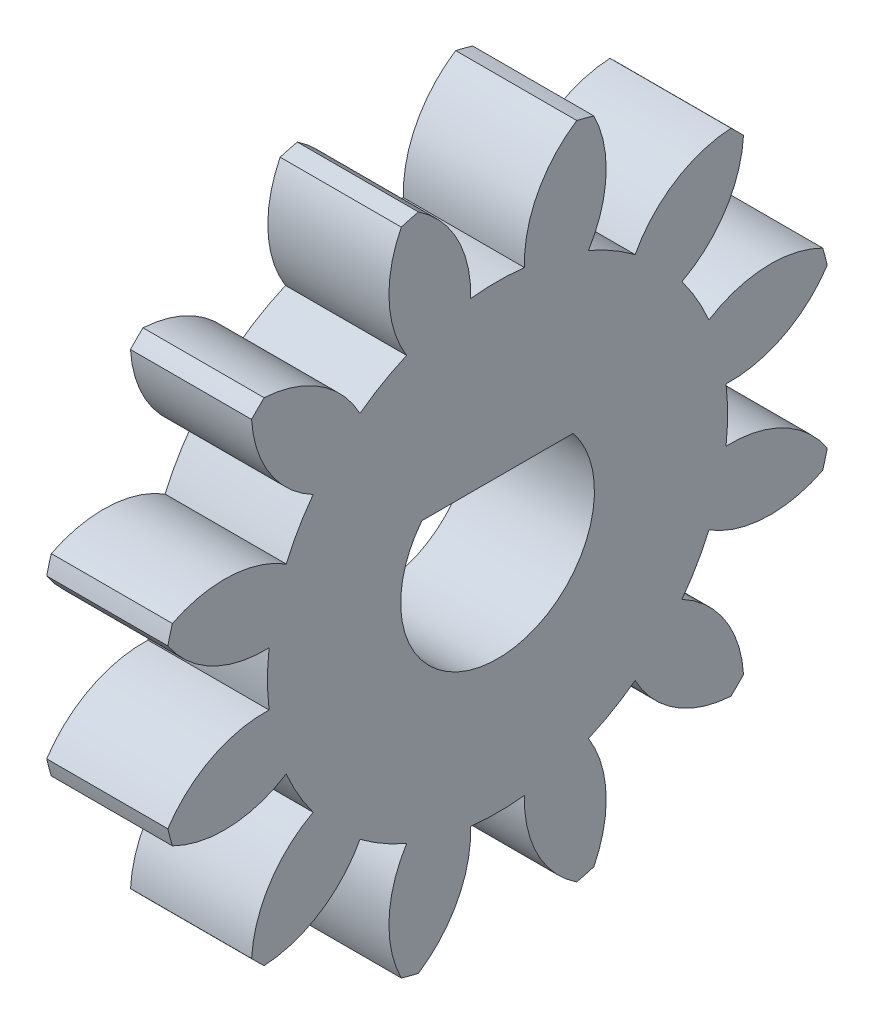
SolidWorks part; units mm, degrees
ref_plane "Plane1" through (0, 0, 0) normal (0, 0, 1) x (1, 0, 0)
ref_plane "Plane2" through (0, 0, 0) normal (0, 1, 0) x (1, 0, 0)
ref_plane "Plane3" through (0, 0, 0) normal (1, 0, 0) x (0, 0, -1)
sketch "HoldingSke" plane through (0, 0, 0) normal (0, 1, 0) x (1, 0, 0)
  line L0 (0, 0) -> (0.4891, -0.104)
  line L1 (-15, 0) -> (100, 0) construction
  line L2 (0, 0) -> (-2.1039, 2.3779)
  line L3 (0, 0) -> (-11.863, 4.5341)
  line L4 (0, 0) -> (8.4473, 1.7955)
  line L5 (0, 0) -> (-46.8476, -17.4728)
  line L6 (0, 0) -> (-4.1448, -2.7965)
  line L7 (-2.1039, 2.3779) -> (8.6586, 51.2059)
  line L8 (-76.2, 54.61) -> (-74.8, 54.61)
  line L9 (-71.009, 38.7566) -> (-53.1078, 45.2721)
  line L10 (-76.2, 71.12) -> (104.1128, 71.12)
  line L11 (0, 0) -> (-5, 0)
  line L12 (-76.2, 101.6) -> (-76.133, 101.6)
  line L13 (24.9733, 27.94) -> (52.9518, 28.4284)
  line L14 (24.9733, 27.94) -> (24.9743, 27.94)
  line L15 (24.9733, 27.94) -> (100.4006, 29.5858)
  line L16 (-63.627, -2) -> (-12.827, -2)
  circle A0 centre (0, 0) radius 4
  circle A1 centre (0, 0) radius 9.499
  circle A2 centre (0, 0) radius 37.5
  circle A3 centre (0, 0) radius 4
  dimension "MHD" = 18.998
  dimension "Hub_dia" = 75
  dimension "Bore" = 8
  dimension "MBD" = 8
  dimension "Num_teeth" = 12
  dimension "Pitch" = 0.5
  dimension "Overall_len" = 50
  dimension "Show_teeth" = 12
  dimension "Thickness" = 5
  dimension "OAL" = 50.0001
  dimension "T_dim" = 1.4
  dimension "Ap" = 20
  dimension "H" = 19.05
  dimension "Pitch_radius" = 180.3128
  dimension "Width" = 5
  dimension "Backlash" = 0.067
  dimension "Addendum_fac" = 1
  dimension "Dedendum_fac" = 1.25
  dimension "Clearance_fac" = 0.25
  dimension "Dedendum_add" = 0.001
  dimension "Module" = 2
sketch "BasProSke" plane through (0, 0, 0) normal (0, 1, 0) x (1, 0, 0)
  line L0 (-10, 0) -> (60, 0) construction
  line L1 (0, 0) -> (0, 14)
  line L2 (0, 0) -> (5, 0)
  line L3 (5, 0) -> (5, 14)
  line L4 (5, 14) -> (0, 14)
  dimension "Thickness" = 5
  dimension "Diameter" = 28
revolve "Base-Revolve" add sketch "BasProSke" angle 360 about L0
sketch "TooCutSke" plane through (0, 0, 0) normal (1, 0, 0) x (0, 0, -1)
  line L1 (0, 0) -> (0, 107) construction
  line L2 (0, 0) -> (-1.6834, 11.8813) construction
  line L3 (0, 0) -> (-6.1662, 23.0126) construction
  line L4 (-1.6834, 11.8813) -> (-3.0831, 11.5063) construction
  arc A0 (1.1119, 9.4337) -> (-1.1119, 9.4337) centre (0, 0) ccw
  arc A1 (3.2981, 13.6321) -> (-3.2981, 13.6321) centre (0, 0) ccw
  circle A2 centre (0, 0) radius 12 construction
  circle A3 centre (0, 0) radius 11.2763 construction
  arc A4 (-1.1119, 9.4337) -> (-3.2981, 13.6321) centre (-5.9089, 9.6042) ccw
  arc A5 (3.2981, 13.6321) -> (1.1119, 9.4337) centre (5.9089, 9.6042) ccw
  dimension "Root_dia" = 18.998
  dimension "Overcut_dia" = 28.0508
  dimension "Pitch_dia" = 24
  dimension "Base_dia" = 22.5526
  dimension "Flank_rad" = 4.8
  dimension "Half_ang" = 15
  dimension "Half_CT" = 1.4491
extrude "ToothCut" cut sketch "TooCutSke" along normal through all
fillet "Breaks" [suppressed] radius 0.04
fillet "RootFillets" [suppressed] radius 0.501
pattern_circular "TeethCuts" count 12 every 30 about axis through (-10, 0, 0) along (1, 0, 0) of "ToothCut", "RootFillets", "Breaks"
sketch "HubNeaOneSke" plane through (0, 0, 0) normal (-1, 0, 0) x (0, 0, 1)
  circle A0 centre (0, 0) radius 9.499
  dimension "Diameter" = 18.998
extrude "HubNearOne" [suppressed] add sketch "HubNeaOneSke" along normal blind 45.0001
sketch "HubNeaBotSke" plane through (0, 0, 0) normal (-1, 0, 0) x (0, 0, 1)
  circle A0 centre (0, 0) radius 9.499
  dimension "Diameter" = 18.998
extrude "HubNearBoth" [suppressed] add sketch "HubNeaBotSke" along normal blind 22.5
ref_plane "FarPln" through (5, 0, 0) normal (1, 0, 0) x (0, 0, -1)
sketch "HubFarSke" plane through (5, 0, 0) normal (1, 0, 0) x (0, 0, -1)
  circle A0 centre (0, 0) radius 9.499
  dimension "Diameter" = 18.998
extrude "HubFar" [suppressed] add sketch "HubFarSke" along normal blind 22.5
sketch "BorSke" plane through (0, 0, 0) normal (1, 0, 0) x (0, 0, -1)
  circle A0 centre (0, 0) radius 4
  dimension "Diameter" = 8
extrude "Bore" cut sketch "BorSke" along normal mid plane 100.0001
sketch "KeySke" plane through (0, 0, 0) normal (1, 0, 0) x (0, 0, -1)
  line L0 (-1.5, 0) -> (-1.5, 5.4)
  line L1 (-1.5, 5.4) -> (1.5, 5.4)
  line L2 (1.5, 5.4) -> (1.5, 0)
  line L3 (0, 0) -> (0, 34) construction
  line L4 (-1.5, 0) -> (1.5, 0)
  dimension "Offset" = 5.4
  dimension "Width" = 3
extrude "Keyway" [suppressed] cut sketch "KeySke" along normal mid plane 100.0001
pattern_circular "Keyway2" [suppressed] count 2 every 90 about axis through (-10, 0, 0) along (1, 0, 0)
sketch "Sketch1" plane through (5, 0, 0) normal (1, 0, 0) x (0, 0, -1)
  line L0 (-3.1225, 2.5) -> (3.1225, 2.5)
  circle A0 centre (0, 0) radius 4 construction
  arc A1 (3.1225, 2.5) -> (-3.1225, 2.5) centre (0, 0) ccw
  dimension "D1" = 2.5
extrude "Boss-Extrude1" add sketch "Sketch1" against normal blind 5
equation "' \"Module@HoldingSke\" = 6.35"
equation "' \"Num_teeth@HoldingSke\" = 12"
equation "' \"Ap@HoldingSke\" =  20"
equation "' \"Ap@HoldingSke\" = 20"
equation "' \"Width@HoldingSke\" = 0.5 * 25.4"
equation "' \"Hub_dia@HoldingSke\"= 1 * 25.4"
equation "' \"Hub_dia@HoldingSke\" = 1 * 25.4"
equation "' \"Overall_len@HoldingSke\" = 1.0 * 25.4"
equation "' \"Bore@HoldingSke\" = 0.75 * 25.4"
equation "' \"T_dim@HoldingSke\" = 0.1 * 25.4"
equation "' \"Width@KeySke\" = 0.25 * 25.4"
equation "' \"Show_teeth@HoldingSke\" = 13"
equation "' \"Backlash@HoldingSke\" = 0.009 * 25.4"
equation "' \"Addendum_fac@HoldingSke\" = 1.0"
equation "' \"Dedendum_fac@HoldingSke\" = 1.25"
equation "' \"Dedendum_add@HoldingSke\" = 0.00005 * 25.4"
equation "' \"Clearance_fac@HoldingSke\" = 0.25"
equation "\"Pitch@HoldingSke\" = 1 / \"Module@HoldingSke\""
equation "\"Overcut_dia@TooCutSke\" = (\"Num_teeth@HoldingSke\" + 2 * \"Addendum_fac@HoldingSke\") / \"Pitch@HoldingSke\" + 0.002 * 25.4"
equation "\"Pitch_dia@TooCutSke\" = \"Num_teeth@HoldingSke\" / \"Pitch@HoldingSke\""
equation "\"Base_dia@TooCutSke\" = \"Num_teeth@HoldingSke\" / \"Pitch@HoldingSke\" * cos((\"Ap@HoldingSke\"  * 3.14159265 / 180))"
equation "\"Root_dia@TooCutSke\" = (\"Num_teeth@HoldingSke\" + 2) / \"Pitch@HoldingSke\" - 2 * (\"Addendum_fac@HoldingSke\" + \"Dedendum_fac@HoldingSke\") / \"Pitch@HoldingSke\" - \"Dedendum_add@HoldingSke\" * 2"
equation "\"Half_ang@TooCutSke\" = 180 / \"Num_teeth@HoldingSke\""
equation "\"Half_CT@TooCutSke\" = \"Num_teeth@HoldingSke\" / \"Pitch@HoldingSke\" * sin((3.14159265 / 2 / \"Num_teeth@HoldingSke\")) / 2 - 7 * \"Backlash@HoldingSke\" / 4"
equation "\"Flank_rad@TooCutSke\" = \"Num_teeth@HoldingSke\" / \"Pitch@HoldingSke\" / 5"
equation "\"Radius@RootFillets\" = \"Clearance_fac@HoldingSke\" / \"Pitch@HoldingSke\" + \"Dedendum_add@HoldingSke\""
equation "\"Break_rad@Breaks\" = 0.02 / \"Pitch@HoldingSke\""
equation "\"Thickness@HoldingSke\" = \"Width@HoldingSke\""
equation "\"OAL@HoldingSke\" = \"Thickness@HoldingSke\""
equation "\"MHD@HoldingSke\" = (\"Num_teeth@HoldingSke\" + 2) / \"Pitch@HoldingSke\" - 2 * (\"Addendum_fac@HoldingSke\" + \"Dedendum_fac@HoldingSke\")  / \"Pitch@HoldingSke\" - \"Dedendum_add@HoldingSke\" * 2"
equation "\"MBD@HoldingSke\" = (\"Num_teeth@HoldingSke\" + 2) / \"Pitch@HoldingSke\" - 2 * (\"Addendum_fac@HoldingSke\" + \"Dedendum_fac@HoldingSke\")  / \"Pitch@HoldingSke\" - \"Dedendum_add@HoldingSke\" * 2 - 0.002 * 25.4"
equation "\"MHD@HoldingSke\" = ((sgn( \"MHD@HoldingSke\" - \"Hub_dia@HoldingSke\" )-1)*( \"MHD@HoldingSke\" - \"Hub_dia@HoldingSke\" ))/-2+ \"Hub_dia@HoldingSke\""
equation "\"MBD@HoldingSke\" = ((sgn( \"MBD@HoldingSke\" - \"Bore@HoldingSke\" )-1)*( \"MBD@HoldingSke\" - \"Bore@HoldingSke\" ))/-2+ \"Bore@HoldingSke\""
equation "\"OAL@HoldingSke\" = ((sgn( \"OAL@HoldingSke\" - \"Overall_len@HoldingSke\" )+1)*( \"OAL@HoldingSke\" - \"Overall_len@HoldingSke\" ))/2 + \"Overall_len@HoldingSke\" + 0.000002 * 25.4"
equation "\"Num_teeth@TeethCuts\" = int( \"Show_teeth@HoldingSke\" ) + 1"
equation "\"Num_teeth@TeethCuts\" = ((sgn( \"Num_teeth@TeethCuts\" - \"Num_teeth@HoldingSke\" )-1)*( \"Num_teeth@TeethCuts\" - \"Num_teeth@HoldingSke\" ))/-2+ \"Num_teeth@HoldingSke\""
equation "\"Num_teeth@TeethCuts\" = ((sgn( \"Num_teeth@TeethCuts\" - 2.0)+1)*( \"Num_teeth@TeethCuts\" - 2.0))/2 +2.0"
equation "\"Angle@TeethCuts\" = 360.0 / \"Num_teeth@HoldingSke\""
equation "\"Diameter@BasProSke\" = (\"Num_teeth@HoldingSke\" + 2 * \"Addendum_fac@HoldingSke\") / \"Pitch@HoldingSke\""
equation "\"Thickness@BasProSke\"  = \"Thickness@HoldingSke\""
equation "' \"Fillet_rad@BasProSke\" =  \"Thickness@HoldingSke\" * 0.05"
equation "' \"Fillet_rad@BasProSke\" = \"Thickness@HoldingSke\" * 0.05"
equation "\"MHD@HoldingSke\" = ((sgn( \"MHD@HoldingSke\" - \"Root_dia@TooCutSke\" )-1)*( \"MHD@HoldingSke\" - \"Root_dia@TooCutSke\" ))/-2+ \"Root_dia@TooCutSke\""
equation "\"Diameter@HubNeaOneSke\" = \"MHD@HoldingSke\""
equation "\"Length@HubNearOne\" = \"OAL@HoldingSke\" - \"Thickness@BasProSke\""
equation "\"Diameter@HubNeaBotSke\" = \"MHD@HoldingSke\""
equation "\"Length@HubNearBoth\" = ( \"OAL@HoldingSke\" - \"Thickness@BasProSke\" ) / 2.0"
equation "\"Thickness@FarPln\" = \"Thickness@BasProSke\""
equation "\"Diameter@HubFarSke\" = \"MHD@HoldingSke\""
equation "\"Length@HubFar\" = ( \"OAL@HoldingSke\" - \"Thickness@BasProSke\" ) / 2.0"
equation "\"Diameter@BorSke\" = \"MBD@HoldingSke\""
equation "\"D1@Bore\" = \"OAL@HoldingSke\" * 2.0"
equation "\"D1@Keyway\" = \"OAL@HoldingSke\" * 2.0"
equation "\"Offset@KeySke\" = \"T_dim@HoldingSke\" + \"MBD@HoldingSke\" / 2.0"
